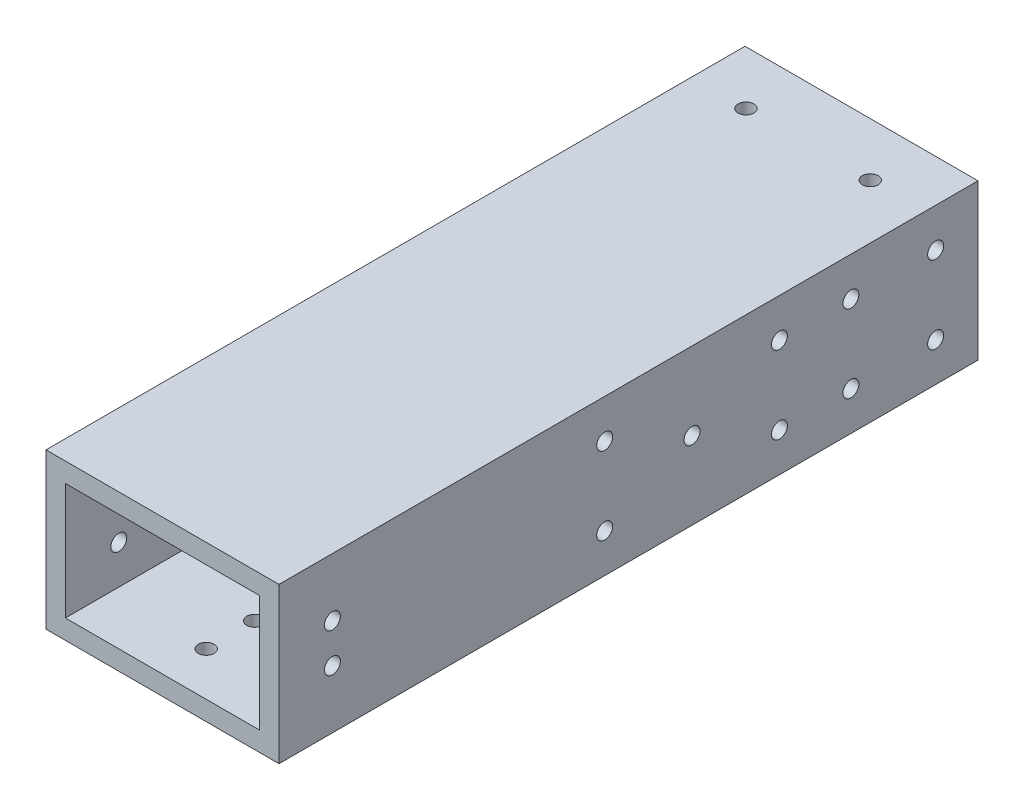
SolidWorks part; units mm, degrees
ref_plane "Front Plane" through (0, 0, 0) normal (0, 0, 1) x (1, 0, 0)
ref_plane "Top Plane" through (0, 0, 0) normal (0, 1, 0) x (1, 0, 0)
ref_plane "Right Plane" through (0, 0, 0) normal (1, 0, 0) x (0, 0, -1)
sketch "Sketch1" plane through (0, 0, 0) normal (0, 0, 1) x (1, 0, 0)
  line L8 (38.1, 737.3561) -> (38.1, 788.1561) construction
  line L12 (-38.1, 788.1561) -> (-38.1, 737.3561) construction
  line L16 (-47.625, 788.1561) -> (-38.1, 788.1561) construction
  line L17 (31.75, 743.7061) -> (-31.75, 743.7061)
  line L18 (38.1, 737.3561) -> (-38.1, 737.3561)
  line L19 (38.1, 737.3561) -> (38.1, 788.1561)
  line L20 (38.1, 788.1561) -> (-38.1, 788.1561)
  line L21 (-38.1, 737.3561) -> (-38.1, 788.1561)
  line L22 (-31.75, 743.7061) -> (-31.75, 781.8061)
  line L23 (31.75, 781.8061) -> (-31.75, 781.8061)
  line L24 (31.75, 743.7061) -> (31.75, 781.8061)
  line L25 (-47.625, 788.1561) -> (-38.1, 788.1561) construction
  dimension "D2" = 50.8
  dimension "D3" = 76.2
  dimension "D1" = 6.35
extrude "Boss-Extrude1" add sketch "Sketch1" against normal blind 76.2 and the other way blind 152.4
sketch "Sketch2" plane through (0, 0, 0) normal (1, 0, 0) x (0, 0, -1)
  line L1 (20.784, 737.7456) -> (20.784, 781.8061) construction
  line L2 (76.2, 737.3561) -> (48.492, 762.7561) construction
  line L3 (20.784, 762.7561) -> (76.2, 762.7561) construction
  line L4 (76.2, 788.1561) -> (-152.4, 788.1561)
  line L5 (76.2, 737.3561) -> (76.2, 788.1561)
  line L6 (-152.4, 737.3561) -> (76.2, 737.3561)
  line L7 (-152.4, 788.1561) -> (-152.4, 737.3561)
  line L8 (76.2, 788.1561) -> (-152.4, 788.1561) construction
  line L9 (76.2, 737.3561) -> (76.2, 788.1561) construction
  line L10 (-152.4, 737.3561) -> (76.2, 737.3561) construction
  line L11 (-152.4, 788.1561) -> (-152.4, 737.3561) construction
  line L12 (48.492, 762.7561) -> (48.492, 737.3561) construction
  line L13 (20.784, 737.7456) -> (20.784, 781.8061) construction
  circle A0 centre (-45.891, 775.4561) radius 3.175 construction
  circle A1 centre (-45.891, 750.0561) radius 3.175 construction
  circle A2 centre (-17.316, 762.7561) radius 3.175 construction
  circle A3 centre (11.259, 775.4561) radius 3.175 construction
  circle A4 centre (11.259, 750.0561) radius 3.175 construction
  circle A5 centre (-45.891, 775.4561) radius 3.175 construction
  circle A6 centre (-45.891, 750.0561) radius 3.175 construction
  circle A7 centre (-17.316, 762.7561) radius 3.175 construction
  circle A8 centre (11.259, 775.4561) radius 3.175 construction
  circle A9 centre (11.259, 750.0561) radius 3.175 construction
  circle A10 centre (62.346, 750.0561) radius 2.6035
  circle A11 centre (34.638, 750.0561) radius 2.6035
  circle A12 centre (34.638, 775.4561) radius 2.6035
  circle A13 centre (62.346, 775.4561) radius 2.6035
  circle A14 centre (11.259, 750.0561) radius 2.6035
  circle A15 centre (11.259, 775.4561) radius 2.6035
  circle A16 centre (-17.316, 762.7561) radius 2.6035
  circle A17 centre (-45.891, 775.4561) radius 2.6035
  circle A18 centre (-45.891, 750.0561) radius 2.6035
  dimension "D2" = 5.207
  dimension "D3" = 5.207
  dimension "D1" = 0
extrude "Cut-Extrude1" cut sketch "Sketch2" against normal through all both and the other way through all
sketch "Sketch3" plane through (38.1, 0, 0) normal (1, 0, 0) x (0, 0, -1)
  circle A0 centre (-134.9375, 769.1061) radius 3.175 construction
  circle A1 centre (-134.9375, 756.4061) radius 3.175 construction
  circle A2 centre (-134.9375, 769.1061) radius 3.175 construction
  circle A3 centre (-134.9375, 756.4061) radius 3.175 construction
  circle A4 centre (-134.9375, 769.1061) radius 2.6035
  circle A5 centre (-134.9375, 756.4061) radius 2.6035
  dimension "D1" = 5.207
extrude "Cut-Extrude2" cut sketch "Sketch3" against normal through all
sketch "Sketch4" plane through (0, 788.1561, 0) normal (0, 1, 0) x (1, 0, 0)
  circle A0 centre (-20.32, 58.7375) radius 3.175 construction
  circle A1 centre (20.32, 58.7375) radius 3.175 construction
  circle A2 centre (-20.32, 58.7375) radius 3.175 construction
  circle A3 centre (20.32, 58.7375) radius 3.175 construction
  circle A4 centre (20.32, 58.7375) radius 2.6035
  circle A5 centre (-20.32, 58.7375) radius 2.6035
  dimension "D1" = 5.207
extrude "Cut-Extrude3" cut sketch "Sketch4" against normal through all
sketch "Sketch5" plane through (0, 737.3561, 0) normal (0, -1, 0) x (1, 0, 0)
  line L0 (-3.302, 120.65) -> (-3.302, 139.7) construction
  line L1 (3.302, 120.65) -> (3.302, 139.7) construction
  line L2 (-3.302, 120.65) -> (-3.302, 139.7) construction
  line L3 (3.302, 120.65) -> (3.302, 139.7) construction
  line L4 (0, 139.7) -> (0, 120.65) construction
  line L5 (-3.302, 130.175) -> (3.302, 130.175) construction
  arc A0 (-3.302, 120.65) -> (3.302, 120.65) centre (0, 120.65) ccw construction
  arc A1 (3.302, 139.7) -> (-3.302, 139.7) centre (0, 139.7) ccw construction
  arc A2 (-3.302, 120.65) -> (3.302, 120.65) centre (0, 120.65) ccw construction
  arc A3 (3.302, 139.7) -> (-3.302, 139.7) centre (0, 139.7) ccw construction
  circle A4 centre (0, 138.1125) radius 2.6035
  circle A5 centre (0, 122.2375) radius 2.6035
  dimension "D1" = 5.207
  dimension "D2" = 1.5875
extrude "Cut-Extrude4" cut sketch "Sketch5" against normal up to next
